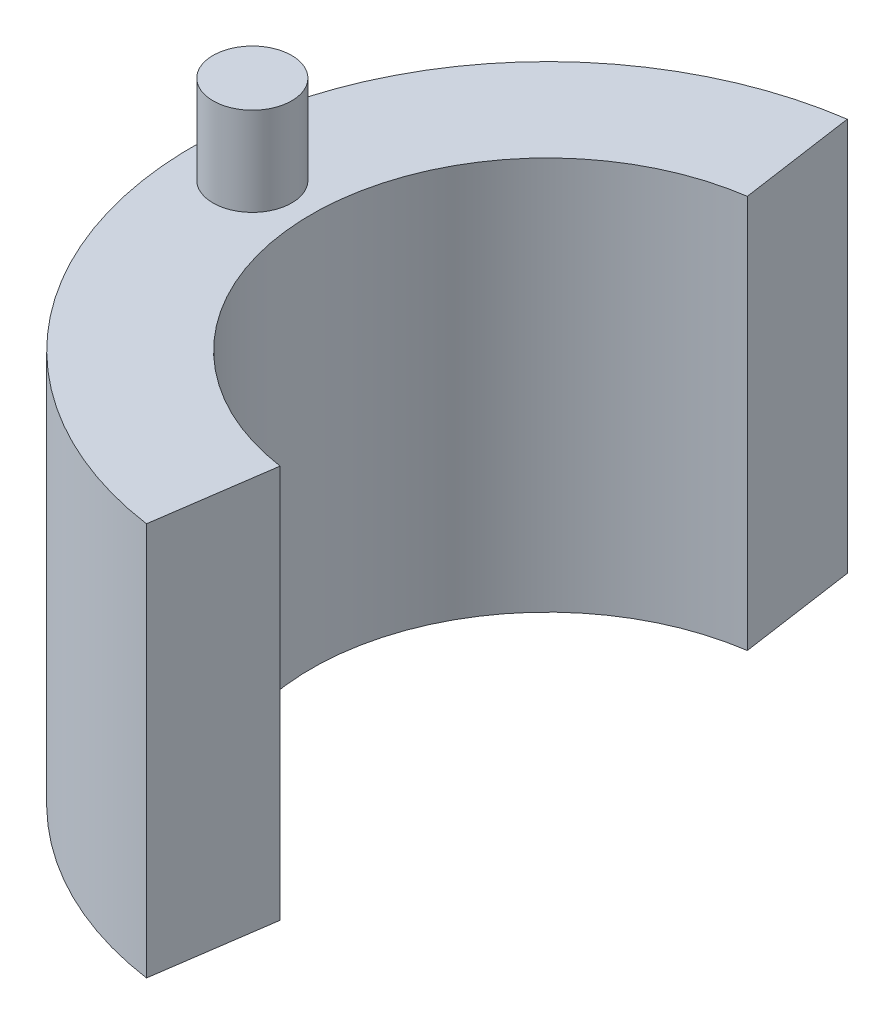
SolidWorks part; units mm, degrees
ref_plane "Front Plane" through (0, 0, 0) normal (0, 0, 1) x (1, 0, 0)
ref_plane "Top Plane" through (0, 0, 0) normal (0, 1, 0) x (1, 0, 0)
ref_plane "Right Plane" through (0, 0, 0) normal (1, 0, 0) x (0, 0, -1)
sketch "Sketch1" plane through (0, 0, 0) normal (0, 1, 0) x (1, 0, 0)
  line L0 (-3.991, 0) -> (-2.2826, 0)
  line L1 (-55, 0) -> (55, 0) construction
  line L2 (-0.8556, 5.9387) -> (-1.2834, 8.908)
  line L3 (-0.8556, -5.9387) -> (-1.2834, -8.908)
  circle A0 centre (0, 0) radius 6
  circle A1 centre (0, 0) radius 9
extrude "Boss-Extrude1" add sketch "Sketch1" along normal blind 10 contours L2 A1 L3 A0
sketch "Sketch2" plane through (0, 10, 0) normal (0, 1, 0) x (1, 0, 0)
  line L0 (-6, 0) -> (-9, 0) construction
  arc A0 (-0.8556, 5.9387) -> (-0.8556, -5.9387) centre (0, 0) ccw construction
  arc A1 (-1.2834, 8.908) -> (-1.2834, -8.908) centre (0, 0) ccw construction
  circle A2 centre (-7.5, 0) radius 1
extrude "Boss-Extrude2" add sketch "Sketch2" along normal blind 2.25
